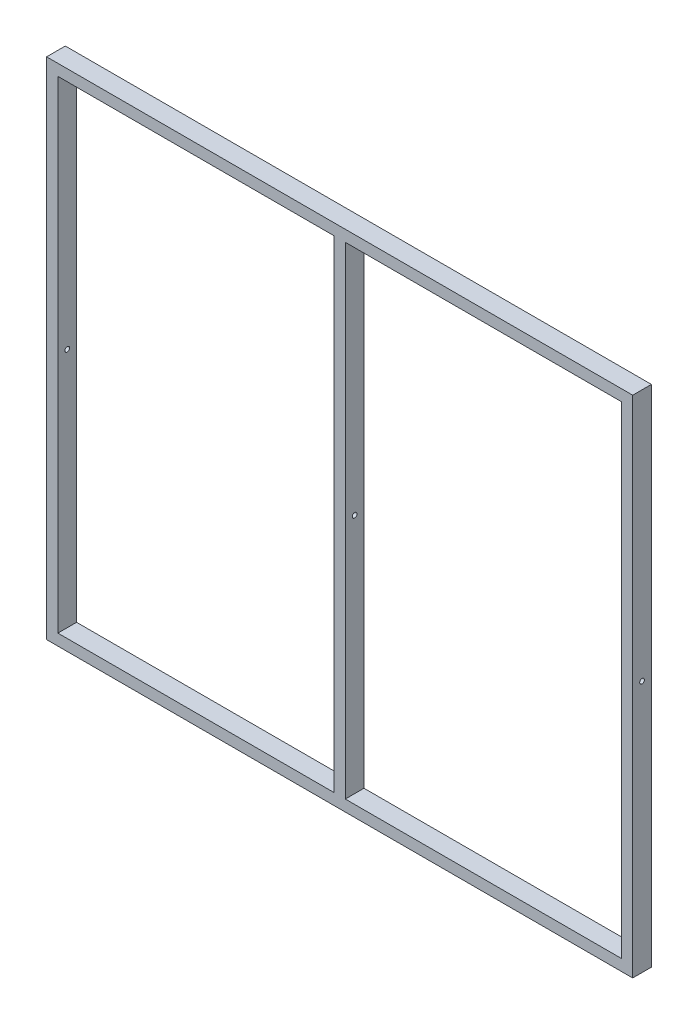
SolidWorks part; units mm, degrees
ref_plane "Front" through (0, 0, 0) normal (0, 0, 1) x (1, 0, 0)
ref_plane "Top" through (0, 0, 0) normal (0, 1, 0) x (1, 0, 0)
ref_plane "Right" through (0, 0, 0) normal (1, 0, 0) x (0, 0, -1)
sketch "Esquisse1" plane through (0, 0, 0) normal (0, 0, 1) x (1, 0, 0)
  line L0 (987, 0) -> (987, 1700) construction
  line L1 (0, 0) -> (1974, 0)
  line L2 (0, 0) -> (0, 1700)
  line L3 (0, 1700) -> (1974, 1700)
  line L4 (1974, 0) -> (1974, 1700)
  line L5 (38, 1662) -> (968, 1662)
  line L6 (38, 1662) -> (38, 38)
  line L7 (38, 38) -> (968, 38)
  line L8 (968, 1662) -> (968, 38)
  line L9 (968, 850) -> (987, 850) construction
  line L10 (1006, 1662) -> (1006, 38)
  line L11 (1936, 38) -> (1006, 38)
  line L12 (1936, 1662) -> (1936, 38)
  line L13 (1936, 1662) -> (1006, 1662)
  line L14 (1974, 0) -> (1974, 1700)
  dimension "D1" = 38
  dimension "D2" = 38
  dimension "D3" = 1700
  dimension "D4" = 930
  dimension "D5" = 38
extrude "Boss.-Extru.1" add sketch "Esquisse1" along normal blind 63 contours L1 L4 L3 L2 L13 L12 L11 L10 L5 L8 L7 L6
sketch "Esquisse2" plane through (1974, 0, 0) normal (1, 0, 0) x (0, 0, -1)
  line L0 (-63, 850) -> (0, 850) construction
  line L1 (-63, 0) -> (-63, 1700) construction
  line L2 (0, 0) -> (0, 1700) construction
  circle A0 centre (-31.5, 850) radius 8
  dimension "D1" = 16
extrude "Enlèv. mat.-Extru.1" cut sketch "Esquisse2" against normal through all
